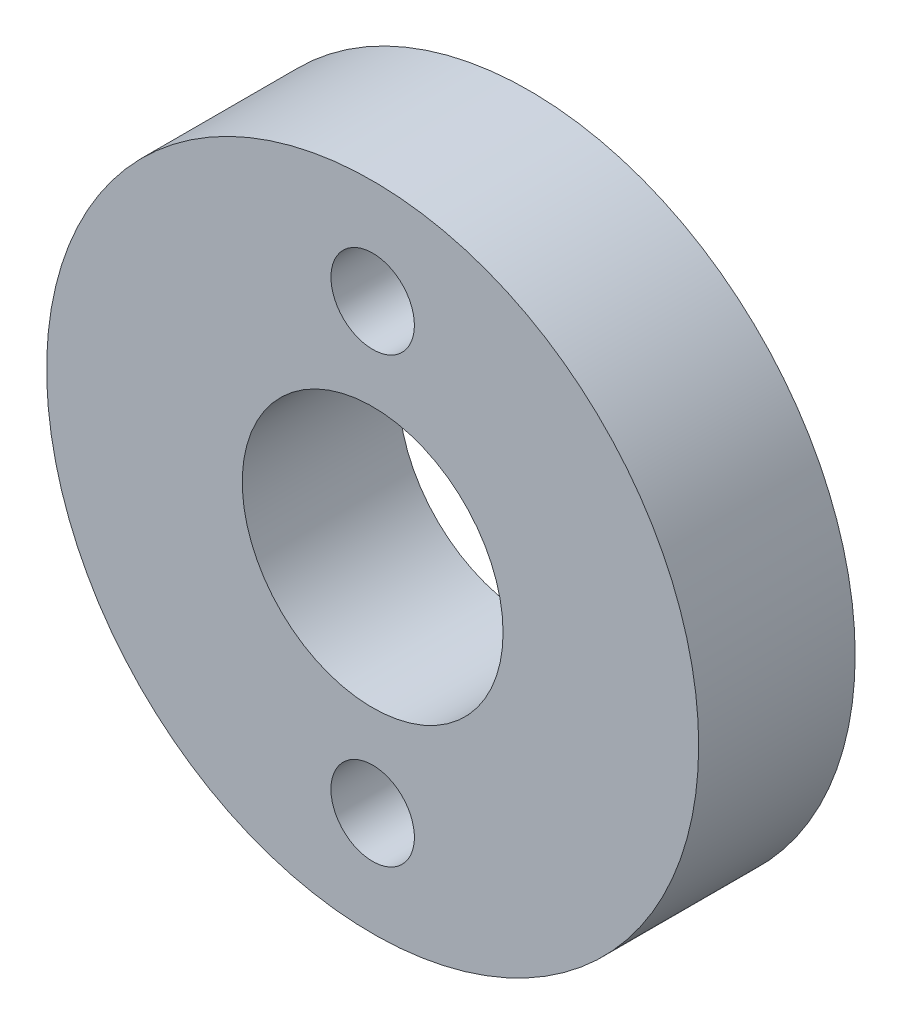
SolidWorks part; units mm, degrees
ref_plane "正面" through (0, 0, 0) normal (0, 0, 1) x (1, 0, 0)
ref_plane "平面" through (0, 0, 0) normal (0, 1, 0) x (1, 0, 0)
ref_plane "右側面" through (0, 0, 0) normal (1, 0, 0) x (0, 0, -1)
sketch "ｽｹｯﾁ1" plane through (0, 0, 0) normal (0, 0, 1) x (1, 0, 0)
  circle A0 centre (0, 0) radius 12.5
  dimension "D1" = 25
extrude "ﾎﾞｽ - 押し出し1" add sketch "ｽｹｯﾁ1" along normal mid plane 6
sketch "ｽｹｯﾁ2" plane through (0, 0, 0) normal (0, 0, 1) x (1, 0, 0)
  circle A0 centre (0, 0) radius 5
  dimension "D1" = 10
extrude "ｶｯﾄ - 押し出し1" cut sketch "ｽｹｯﾁ2" against normal through all both and the other way through all
sketch "ｽｹｯﾁ3" plane through (0, 0, 3) normal (0, 0, 1) x (1, 0, 0)
  circle A0 centre (0, 8.5) radius 1.6
  point P2 (0, 0)
  point P4 (0, 8.0498)
  dimension "D1" = 3.2
  dimension "D2" = 8.5
extrude "ｶｯﾄ - 押し出し2" cut sketch "ｽｹｯﾁ3" against normal through all both
pattern_circular "円形ﾊﾟﾀｰﾝ1" count 2 over 360 about axis through (0, 0, 0) along (0, 0, 1) of "ｶｯﾄ - 押し出し2"
